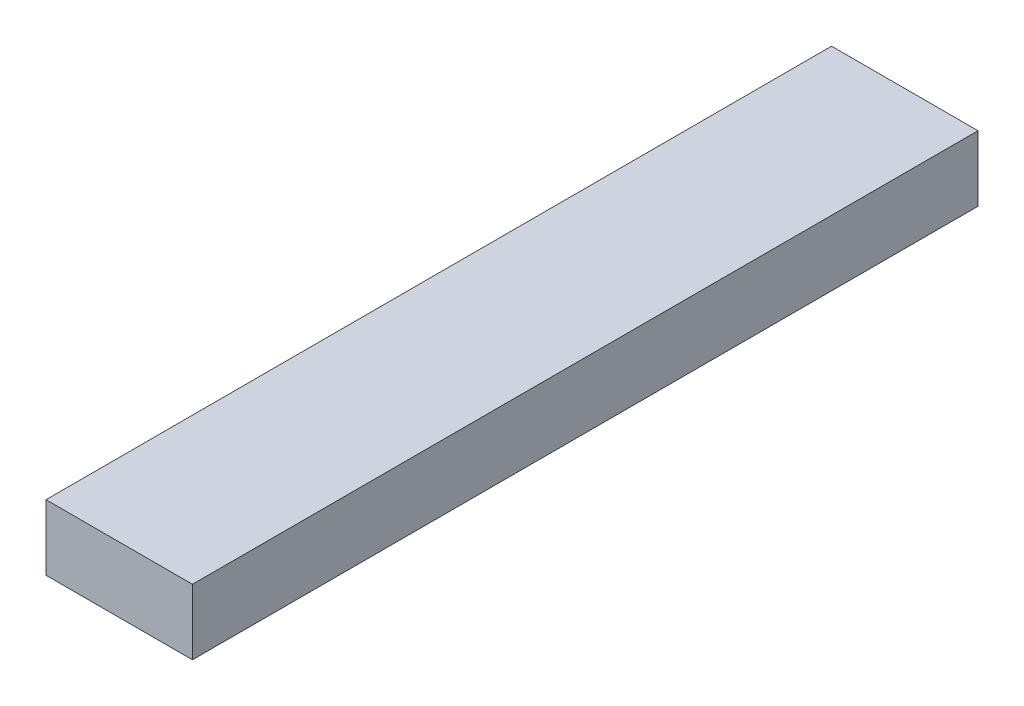
SolidWorks part; units mm, degrees
ref_plane "Front Plane" through (0, 0, 0) normal (1, 0, 0) x (0, 1, 0)
ref_plane "Top Plane" through (0, 0, 0) normal (0, 0, 1) x (0, 1, 0)
ref_plane "Right Plane" through (0, 0, 0) normal (0, 1, 0) x (-1, 0, 0)
sketch "Sketch1" plane through (0, 0, 0) normal (0, 0, 1) x (0, 1, 0)
  line L1 (-8.3312, -18.6436) -> (8.3312, -18.6436)
  line L2 (-8.3312, -18.6436) -> (-8.3312, 18.6436)
  line L3 (-8.3312, 18.6436) -> (8.3312, 18.6436)
  line L4 (8.3312, -18.6436) -> (8.3312, 18.6436)
  line L5 (-8.3312, -18.6436) -> (8.3312, 18.6436) construction
  line L6 (-8.3312, 18.6436) -> (8.3312, -18.6436) construction
  point P0 (0, 0)
  dimension "D1" = 16.6624
  dimension "D2" = 37.2872
extrude "Boss-Extrude1" add sketch "Sketch1" along normal mid plane 200
